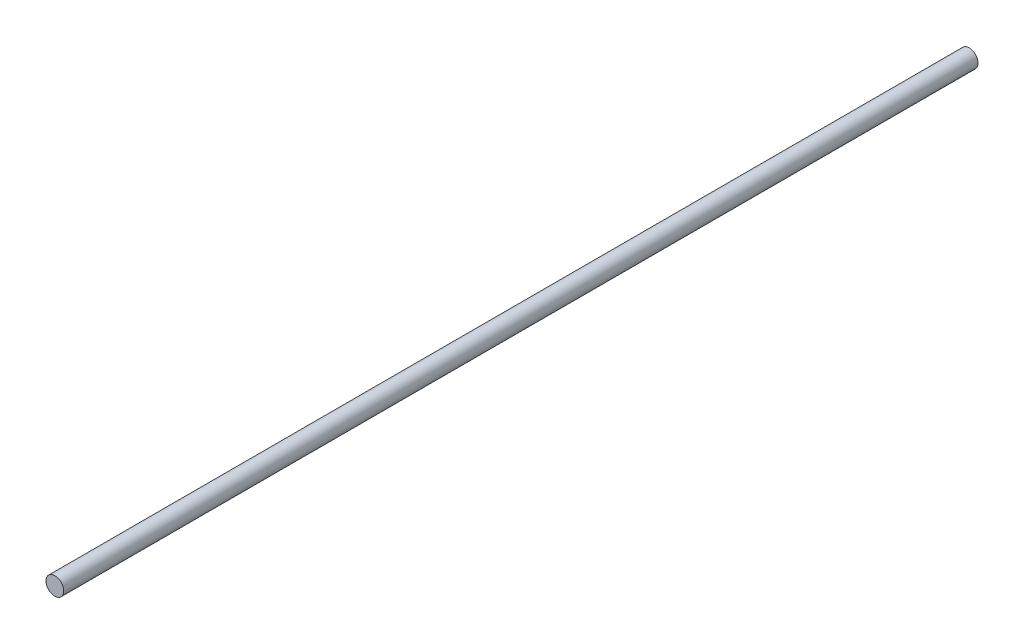
SolidWorks part; units mm, degrees
ref_plane "Front Plane" through (0, 0, 0) normal (0, 0, 1) x (1, 0, 0)
ref_plane "Top Plane" through (0, 0, 0) normal (0, 1, 0) x (1, 0, 0)
ref_plane "Right Plane" through (0, 0, 0) normal (1, 0, 0) x (0, 0, -1)
sketch "Sketch1" plane through (0, 0, 0) normal (0, 0, 1) x (1, 0, 0)
  circle A0 centre (0, 0) radius 1.475
extrude "Boss-Extrude1" add sketch "Sketch1" along normal blind 152.24 contours A0
